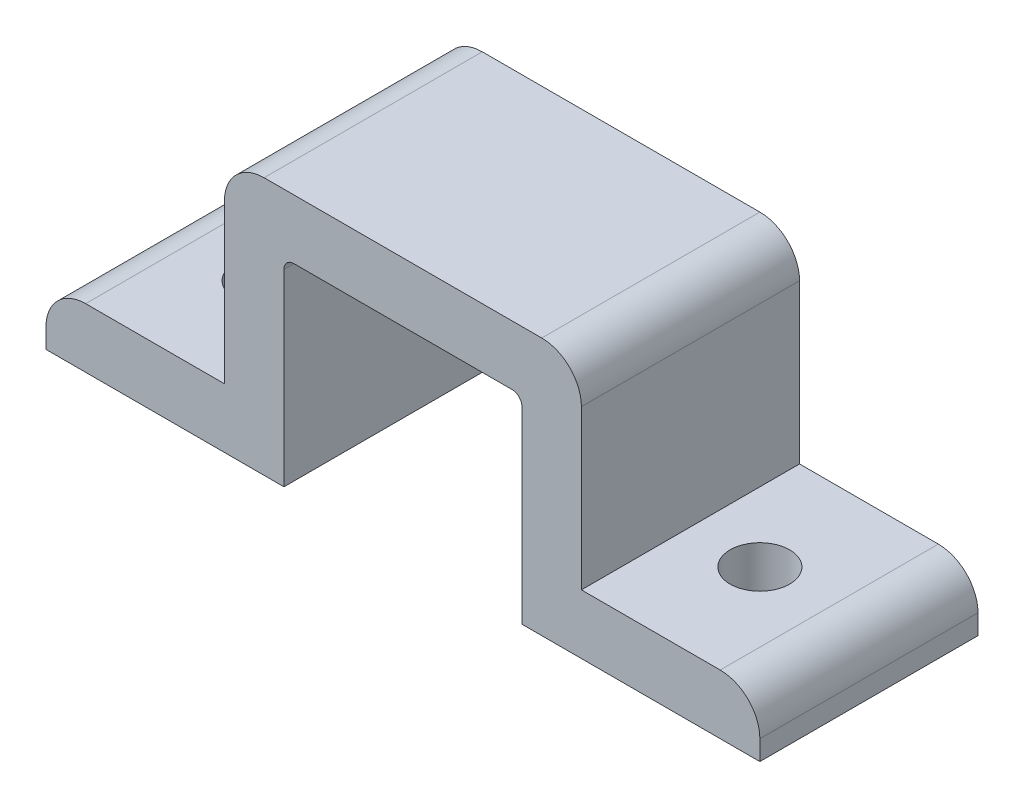
SolidWorks part; units mm, degrees
ref_plane "Front Plane" through (0, 0, 0) normal (0, 0, 1) x (1, 0, 0)
ref_plane "Top Plane" through (0, 0, 0) normal (0, 1, 0) x (1, 0, 0)
ref_plane "Right Plane" through (0, 0, 0) normal (1, 0, 0) x (0, 0, -1)
sketch "Sketch1" plane through (0, 0, 0) normal (0, 0, 1) x (1, 0, 0)
  line L0 (0, 0) -> (0, 10) construction
  line L1 (6, 10) -> (-6, 10)
  line L2 (-6, 10) -> (-6, 0)
  line L3 (-6, 0) -> (-18, 0)
  line L4 (-18, 0) -> (-18, 3)
  line L5 (-18, 3) -> (-9, 3)
  line L6 (-9, 3) -> (-9, 13)
  line L7 (-9, 13) -> (9, 13)
  line L8 (18, 0) -> (18, 3)
  line L9 (18, 3) -> (9, 3)
  line L10 (9, 3) -> (9, 13)
  line L11 (6, 0) -> (18, 0)
  line L12 (6, 10) -> (6, 0)
  point P14 (0, 13)
  dimension "D1" = 13
  dimension "D2" = 10
  dimension "D3" = 9
  dimension "D4" = 6
  dimension "D5" = 18
  dimension "D6" = 18
  dimension "D7" = 3
extrude "Boss-Extrude1" add sketch "Sketch1" along normal blind 11
fillet "Fillet1" radius 2 4 edges at (-18, 3, 5.5) (-9, 13, 5.5) (9, 13, 5.5) (18, 3, 5.5)
fillet "Fillet2" radius 0.5 2 edges at (-6, 10, 5.5) (6, 10, 5.5)
sketch "Sketch2" plane through (0, 3, 0) normal (0, 1, 0) x (1, 0, 0)
  line L0 (-12.5, 0) -> (-12.5, -11) construction
  line L1 (-9, 0) -> (-16, 0) construction
  line L2 (-9, -11) -> (-16, -11) construction
  line L3 (-16, -5.5) -> (-9, -5.5) construction
  line L4 (-16, 0) -> (-16, -11) construction
  line L5 (-9, -11) -> (-9, 0) construction
  line L6 (0, 0) -> (0, -11) construction
  line L7 (7, -11) -> (-7, -11) construction
  circle A0 centre (-12.5, -5.5) radius 1.5
  circle A1 centre (12.5, -5.5) radius 1.5
  dimension "D1" = 3
extrude "Cut-Extrude1" cut sketch "Sketch2" against normal up to surface (3 mm away) up to face at (-12, 0, 5.5)
